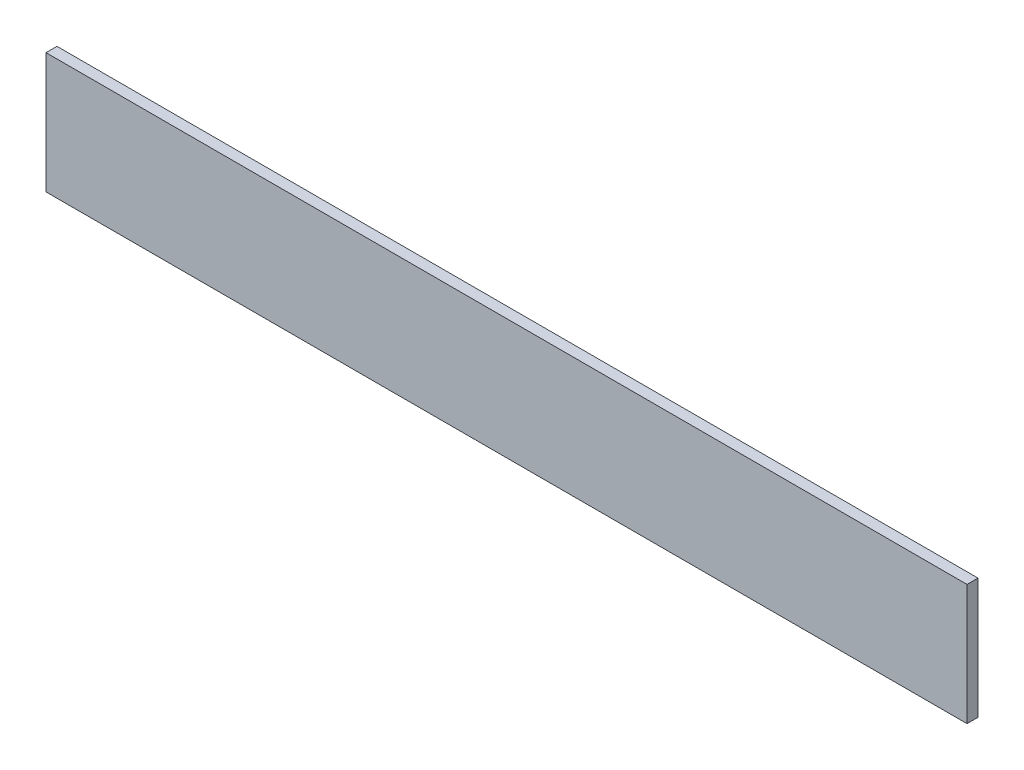
SolidWorks part; units mm, degrees
ref_plane "정면" through (0, 0, 0) normal (0, 0, 1) x (1, 0, 0)
ref_plane "윗면" through (0, 0, 0) normal (0, 1, 0) x (1, 0, 0)
ref_plane "우측면" through (0, 0, 0) normal (1, 0, 0) x (0, 0, -1)
sketch "스케치1" plane through (0, 0, 0) normal (0, 0, 1) x (1, 0, 0)
  line L1 (-210, 27.5) -> (210, 27.5)
  line L2 (-210, 27.5) -> (-210, -27.5)
  line L3 (-210, -27.5) -> (210, -27.5)
  line L4 (210, 27.5) -> (210, -27.5)
  line L5 (-210, 27.5) -> (210, -27.5) construction
  line L6 (-210, -27.5) -> (210, 27.5) construction
  point P0 (0, 0)
  dimension "D1" = 55
  dimension "D2" = 420
extrude "보스-돌출1" add sketch "스케치1" along normal blind 5
